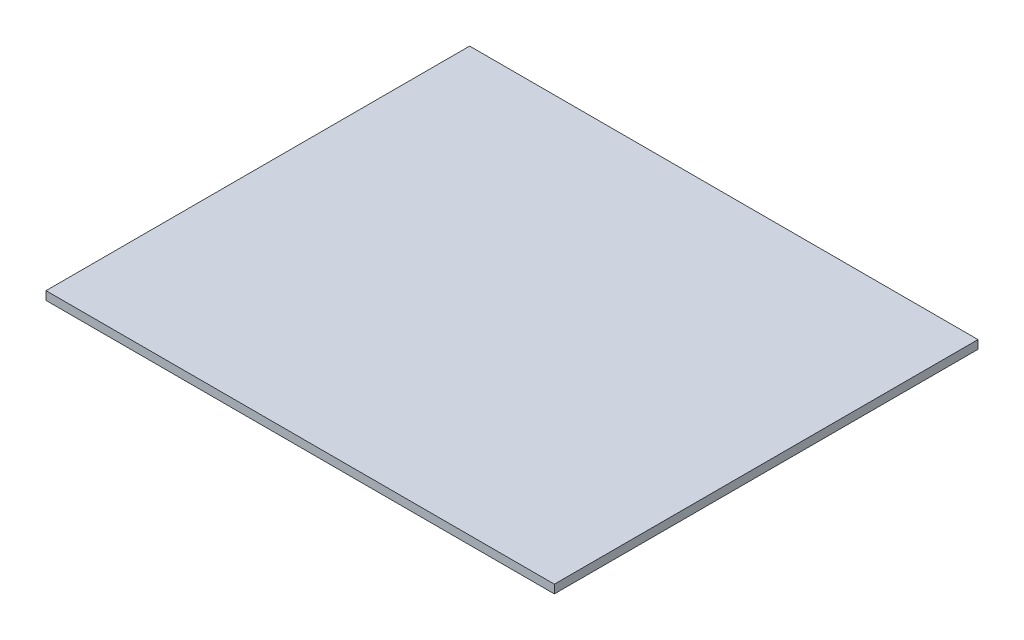
SolidWorks part; units mm, degrees
ref_plane "Front Plane" through (0, 0, 0) normal (0, 0, 1) x (1, 0, 0)
ref_plane "Top Plane" through (0, 0, 0) normal (0, 1, 0) x (1, 0, 0)
ref_plane "Right Plane" through (0, 0, 0) normal (1, 0, 0) x (0, 0, -1)
sketch "Sketch1" plane through (0, 0, 0) normal (0, 1, 0) x (1, 0, 0)
  line L1 (-90, -75) -> (90, -75)
  line L2 (-90, -75) -> (-90, 75)
  line L3 (-90, 75) -> (90, 75)
  line L4 (90, -75) -> (90, 75)
  line L5 (-90, -75) -> (90, 75) construction
  line L6 (-90, 75) -> (90, -75) construction
  point P0 (0, 0)
  dimension "D1" = 180
  dimension "D2" = 150
extrude "Boss-Extrude1" add sketch "Sketch1" along normal blind 3
